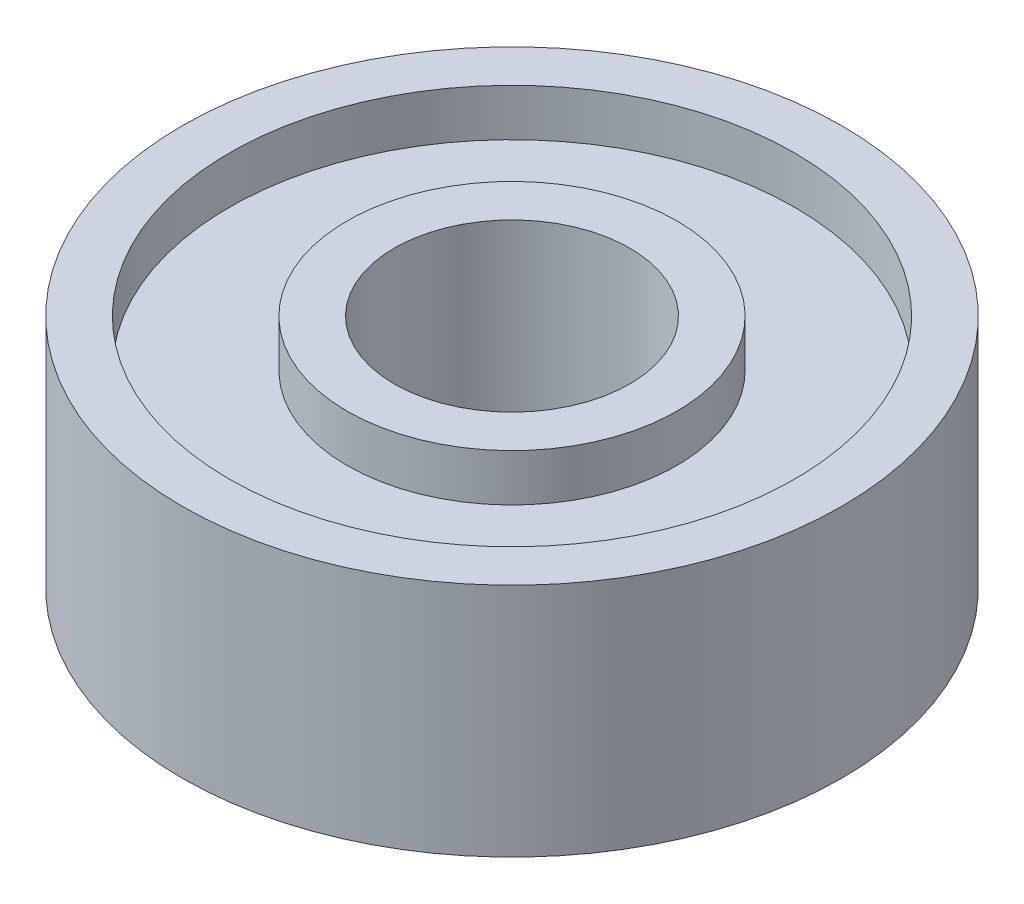
SolidWorks part; units mm, degrees
ref_plane "정면" through (0, 0, 0) normal (0, 0, 1) x (1, 0, 0)
ref_plane "윗면" through (0, 0, 0) normal (0, 1, 0) x (1, 0, 0)
ref_plane "우측면" through (0, 0, 0) normal (1, 0, 0) x (0, 0, -1)
sketch "스케치1" plane through (0, 0, 0) normal (0, 1, 0) x (1, 0, 0)
  circle A0 centre (0, 0) radius 7
  circle A1 centre (0, 0) radius 2.5
extrude "보스-돌출1" add sketch "스케치1" along normal blind 5
sketch "스케치2" plane through (0, 5, 0) normal (0, 1, 0) x (1, 0, 0)
  circle A0 centre (0, 0) radius 6
  circle A1 centre (0, 0) radius 3.5
extrude "컷-돌출1" cut sketch "스케치2" against normal blind 1
sketch "스케치3" plane through (0, 0, 0) normal (0, -1, 0) x (-1, 0, 0)
  circle A0 centre (0, 0) radius 6
  circle A1 centre (0, 0) radius 3.5
extrude "컷-돌출2" cut sketch "스케치3" against normal blind 1
